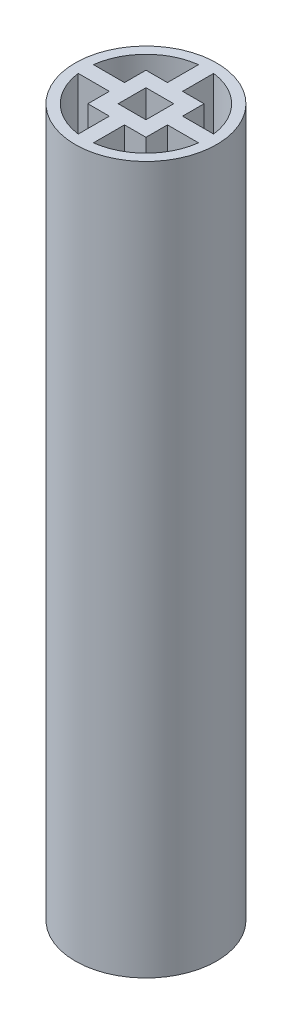
SolidWorks part; units mm, degrees
ref_plane "Front Plane" through (0, 0, 0) normal (0, 0, 1) x (1, 0, 0)
ref_plane "Top Plane" through (0, 0, 0) normal (0, 1, 0) x (1, 0, 0)
ref_plane "Right Plane" through (0, 0, 0) normal (1, 0, 0) x (0, 0, -1)
sketch "Sketch1" plane through (0, 0, 0) normal (0, 1, 0) x (1, 0, 0)
  line L0 (-5.75, 1.5) -> (-11.9059, 1.5)
  line L1 (5.75, -5.75) -> (1.5, -5.75)
  line L2 (5.75, -5.75) -> (5.75, -1.5)
  line L3 (5.75, 5.75) -> (1.5, 5.75)
  line L4 (-5.75, -5.75) -> (-5.75, -1.5)
  line L5 (5.75, -5.75) -> (-5.75, 5.75) construction
  line L6 (5.75, 5.75) -> (-5.75, -5.75) construction
  line L7 (-11.9059, -1.5) -> (-5.75, -1.5)
  line L8 (1.5, 5.75) -> (1.5, 11.9059)
  line L9 (-1.5, 11.9059) -> (-1.5, 5.75)
  line L10 (5.75, -1.5) -> (11.9059, -1.5)
  line L11 (11.9059, 1.5) -> (5.75, 1.5)
  line L12 (-1.5, -5.75) -> (-1.5, -11.9059)
  line L13 (1.5, -11.9059) -> (1.5, -5.75)
  line L14 (-5.75, 1.5) -> (-5.75, 5.75)
  line L15 (-1.5, 5.75) -> (-5.75, 5.75)
  line L16 (5.75, 1.5) -> (5.75, 5.75)
  line L17 (-1.5, -5.75) -> (-5.75, -5.75)
  line L19 (2.75, -2.75) -> (-2.75, -2.75)
  line L20 (2.75, -2.75) -> (2.75, 2.75)
  line L21 (2.75, 2.75) -> (-2.75, 2.75)
  line L22 (-2.75, -2.75) -> (-2.75, 2.75)
  line L23 (2.75, -2.75) -> (-2.75, 2.75) construction
  line L24 (2.75, 2.75) -> (-2.75, -2.75) construction
  circle A0 centre (0, 0) radius 14
  arc A1 (-11.9059, -1.5) -> (-1.5, -11.9059) centre (0, 0) ccw
  arc A3 (-1.5, 11.9059) -> (-11.9059, 1.5) centre (0, 0) ccw
  arc A4 (11.9059, 1.5) -> (1.5, 11.9059) centre (0, 0) ccw
  arc A5 (1.5, -11.9059) -> (11.9059, -1.5) centre (0, 0) ccw
  point P28 (0, 0)
  dimension "D1" = 28
  dimension "D2" = 2
  dimension "D4" = 5.5
  dimension "D3" = 11.5
  dimension "D5" = 3
  dimension "D6" = 1.5
  dimension "D7" = 4
extrude "Body" add sketch "Sketch1" along normal mid plane 140
